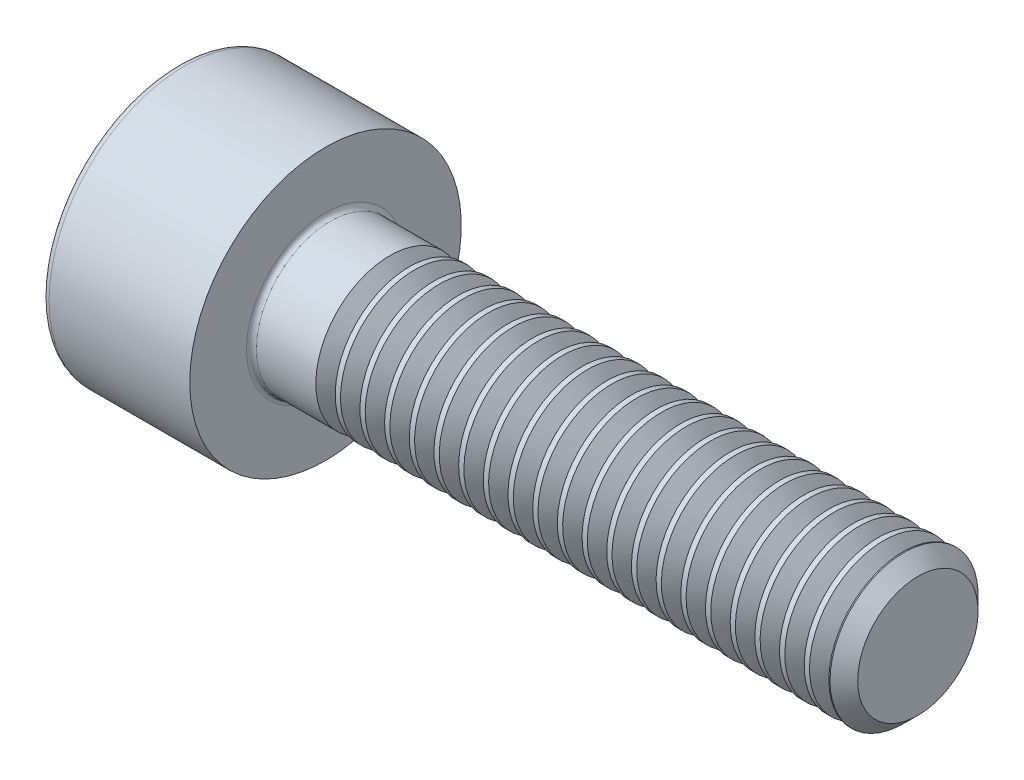
SolidWorks part; units mm, degrees
revolve "Base-Revolve" add sketch "BodySke"
sketch "BodySke" plane through (0, 0, 0) normal (0, 0, 1) x (1, 0, 0)
  line L0 (0, 0) -> (0, 2.75)
  line L1 (0, 2.75) -> (3, 2.75)
  line L2 (3, 2.75) -> (3, 1.5)
  line L3 (3, 1.5) -> (14.7195, 1.5)
  line L4 (15, 1.2195) -> (15, 0)
  line L5 (15, 0) -> (0, 0)
  line L6 (-31.75, 0) -> (127, 0) construction
  line L8 (15, 1.2195) -> (14.7195, 1.5)
  line L10 (15, -1.2195) -> (14.7195, -1.5) construction
  line L11 (3.5, 9.525) -> (3.5, 3.175) construction
  line L12 (3, 9.525) -> (3, 3.175) construction
  line L13 (-45, 9.525) -> (-45, 3.175) construction
  dimension "Head_ht" = 3
  dimension "Length" = 12
  dimension "Body_ch_ang" = 45
  dimension "Diameter" = 3
  dimension "Minor_dia" = 2.439
  dimension "Advance" = 0.5
  dimension "Thread_nom" = 12
  dimension "Thread_length" = 60
  dimension "Head_dia" = 5.5
cosmetic thread "ThreadCosmetic" [suppressed]
fillet "Fillet1" radius 0.1 1 edges at (3, 0, 1.5)
fillet "Fillet2" radius 0.15 1 edges at (0, 0, 2.75)
ref_plane "Plane1" through (0, 0, 0) normal (0, 0, 1) x (1, 0, 0)
ref_plane "Plane2" through (0, 0, 0) normal (0, 1, 0) x (1, 0, 0)
ref_plane "Plane3" through (0, 0, 0) normal (1, 0, 0) x (0, 0, -1)
other "Configuration Table"
sketch "Sketch2" plane through (0, 0, 0) normal (0, 0, 1) x (1, 0, 0)
  line L0 (0, 1.28) -> (1.3, 1.28)
  line L1 (1.3, 1.28) -> (2.039, 0)
  line L2 (-31.75, 0) -> (127, 0) construction
  line L3 (2.039, 0) -> (0, 0)
  line L4 (0, 0) -> (0, 1.28)
  line L6 (0, 0) -> (47.625, 0) construction
  dimension "D1" = 1.28
  dimension "D2" = 60
  dimension "Depth" = 1.3
revolve "Hex-PreBroach" cut sketch "Sketch2" angle 360 about L6
sketch "Sketch3" plane through (0, 0, 0) normal (-1, 0, 0) x (0, 0.5, 0.866)
  line L0 (0.739, 1.28) -> (-0.739, 1.28)
  line L1 (-0.739, 1.28) -> (-1.478, 0)
  line L2 (0.739, 1.28) -> (1.478, 0)
  line L3 (0.739, -1.28) -> (1.478, 0)
  line L4 (0.739, -1.28) -> (-0.739, -1.28)
  line L5 (-0.739, -1.28) -> (-1.478, 0)
  dimension "D1" = 1.28
  dimension "D2" = 1.28
  dimension "Hex_size" = 2.56
extrude "Hex" cut sketch "Sketch3" against normal blind 1.3
sketch "ThdSchSke" plane through (0, 0, 0) normal (0, 0, 1) x (1, 0, 0)
  line L0 (4.5, -1.2195) -> (4.3036, -1.5)
  line L1 (4.5, -1.2195) -> (4.6964, -1.5)
  line L2 (4.6964, -1.5) -> (4.6964, -1.875)
  line L3 (-3.175, 0) -> (5.1513, 0) construction
  line L4 (0, 2.6) -> (0, -2.6) construction
  line L5 (4.6964, -1.875) -> (4.3036, -1.875)
  line L6 (4.3036, -1.875) -> (4.3036, -1.5)
  dimension "Thread_minor" = 2.439
  dimension "Diameter" = 3
  dimension "Start" = 4.5
revolve "ThreadSchematic" cut sketch "ThdSchSke" angle 360 about L3
pattern_linear "ThdSchPat" count 21 spacing 0.5 along (1, 0, 0) of "ThreadSchematic"
equation "\"D2@Sketch3\" = \"Hex_size@Sketch3\" / 2"
equation "\"D1@Sketch3\" = \"Hex_size@Sketch3\" / 2"
equation "\"D1@Sketch2\" = \"Hex_size@Sketch3\" / 2"
equation "\"Thread_minor@ThreadCosmetic\"  =  \"Minor_dia@BodySke\""
equation "\"Depth@Sketch2\" =  \"Key_eng@Hex\""
equation "\"Thread_length@ThreadCosmetic\" = ((sgn( (\"Length@BodySke\" - \"Advance@BodySke\" * 3.0) - \"Thread_nom@BodySke\" )-1)*( (\"Length@BodySke\" - \"Advance@BodySke\" * 3.0) - \"Thread_nom@BodySke\" ))/-2+ \"Thread_nom@BodySke\""
equation "\"Thread_minor@ThdSchSke\" = \"Minor_dia@BodySke\""
equation "\"Diameter@ThdSchSke\" = \"Diameter@BodySke\""
equation "\"Overcut@ThdSchSke\" = \"Diameter@BodySke\" * 1.25"
equation "\"Start@ThdSchSke\" = \"Head_ht@BodySke\" + \"Length@BodySke\" - \"Thread_length@ThreadCosmetic\"  '---Non-countersunk---"
equation "\"Num_threads@ThdSchPat\" = int( \"Thread_length@ThreadCosmetic\" / \"Advance@BodySke\" + 0.999 )  + 1"
equation "\"Advance@ThdSchPat\" = \"Thread_length@ThreadCosmetic\" /  (\"Num_threads@ThdSchPat\" - 1) 'relax it"
equation "\"Num_threads@ThdSchPat\" = \"Num_threads@ThdSchPat\" - sgn( \"Num_threads@ThdSchPat\" - 1) '---chamfered tips only---"
